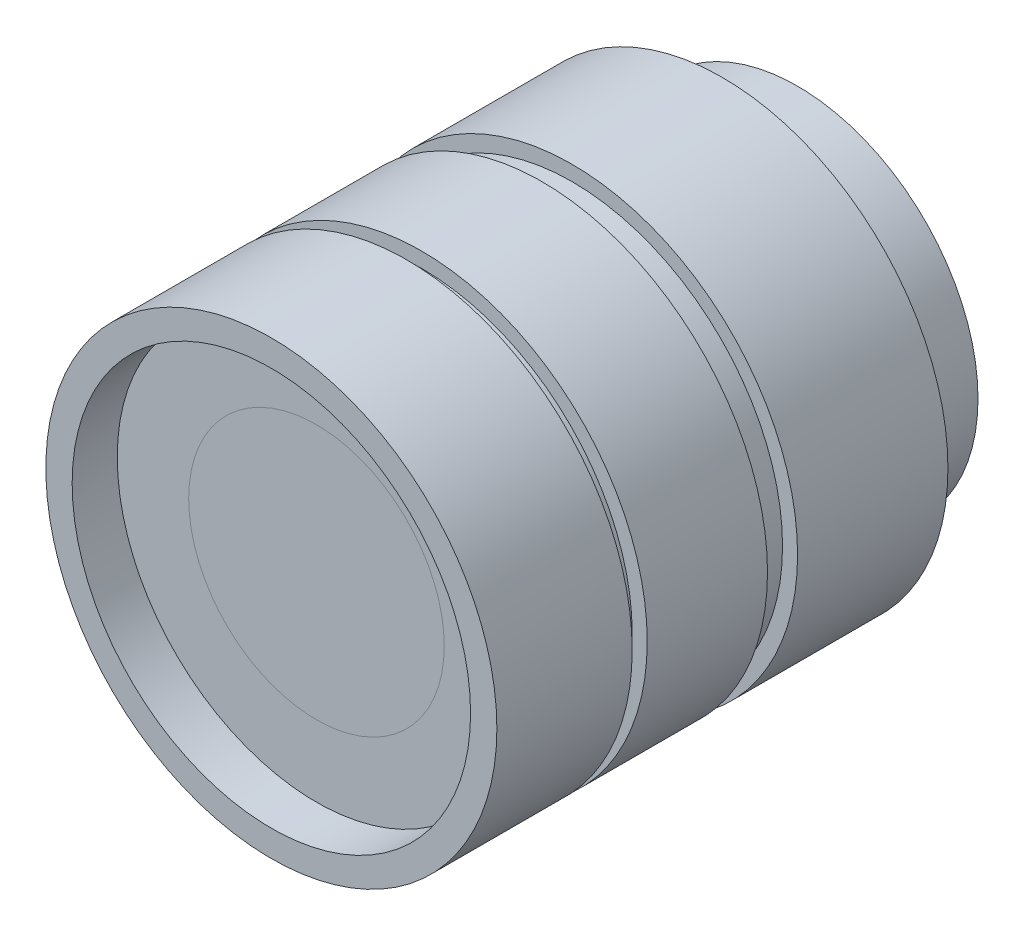
SolidWorks part; units mm, degrees
ref_plane "Front Plane" through (0, 0, 0) normal (0, 0, 1) x (1, 0, 0)
ref_plane "Top Plane" through (0, 0, 0) normal (0, 1, 0) x (1, 0, 0)
ref_plane "Right Plane" through (0, 0, 0) normal (1, 0, 0) x (0, 0, -1)
sketch "Sketch1" plane through (0, 0, 0) normal (0, 0, 1) x (1, 0, 0)
  circle A0 centre (0, 0) radius 15
  dimension "D1" = 30
extrude "Base" add sketch "Sketch1" along normal blind 10
sketch "Sketch2" plane through (0, 0, 10) normal (0, 0, 1) x (1, 0, 0)
  circle A0 centre (0, 0) radius 14
  dimension "D1" = 28
extrude "Boss-Extrude2" add sketch "Sketch2" along normal blind 2
sketch "Sketch3" plane through (0, 0, 12) normal (0, 0, 1) x (1, 0, 0)
  circle A0 centre (0, 0) radius 15
  dimension "D1" = 30
extrude "Boss-Extrude3" add sketch "Sketch3" along normal blind 8
sketch "Sketch4" plane through (0, 0, 20) normal (0, 0, 1) x (1, 0, 0)
  circle A0 centre (0, 0) radius 14
  dimension "D1" = 28
extrude "Boss-Extrude4" add sketch "Sketch4" along normal blind 1
sketch "Sketch5" plane through (0, 0, 21) normal (0, 0, 1) x (1, 0, 0)
  circle A0 centre (0, 0) radius 15
  dimension "D1" = 30
extrude "Boss-Extrude5" add sketch "Sketch5" along normal blind 9
sketch "Sketch6" plane through (0, 0, 30) normal (0, 0, 1) x (1, 0, 0)
  circle A0 centre (0, 0) radius 13.25
  dimension "D1" = 26.5
extrude "Cut-Extrude1" cut sketch "Sketch6" against normal blind 3
sketch "Sketch7" plane through (0, 0, 27) normal (0, 0, 1) x (1, 0, 0)
  circle A0 centre (0, 0) radius 8.5
  dimension "D1" = 17
split line "Split Line1"
sketch "Sketch8" plane through (0, 0, 0) normal (0, 0, -1) x (-1, 0, 0)
  circle A0 centre (0, 0) radius 12
  dimension "D1" = 24
extrude "Boss-Extrude6" add sketch "Sketch8" along normal blind 5 separate body
